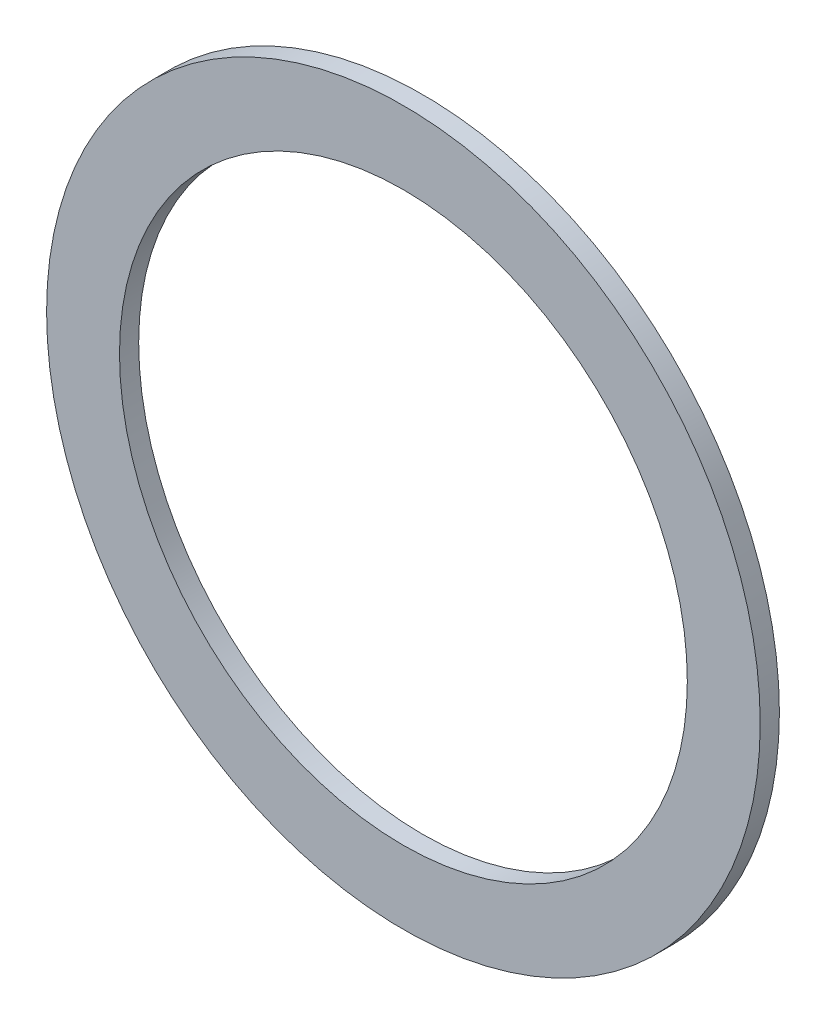
SolidWorks part; units mm, degrees
ref_plane "Ön Düzlem" through (0, 0, 0) normal (0, 0, 1) x (1, 0, 0)
ref_plane "Üst Düzlem" through (0, 0, 0) normal (0, 1, 0) x (1, 0, 0)
ref_plane "Sağ Düzlem" through (0, 0, 0) normal (1, 0, 0) x (0, 0, -1)
sketch "Çizim1" plane through (0, 0, 0) normal (0, 0, 1) x (1, 0, 0)
  circle A0 centre (0, 0) radius 7.4
  circle A1 centre (0, 0) radius 9.3
  dimension "D1" = 18.6
  dimension "D2" = 14.8
extrude "Yükseklik-Ekstrüzyon1" add sketch "Çizim1" along normal blind 0.5
